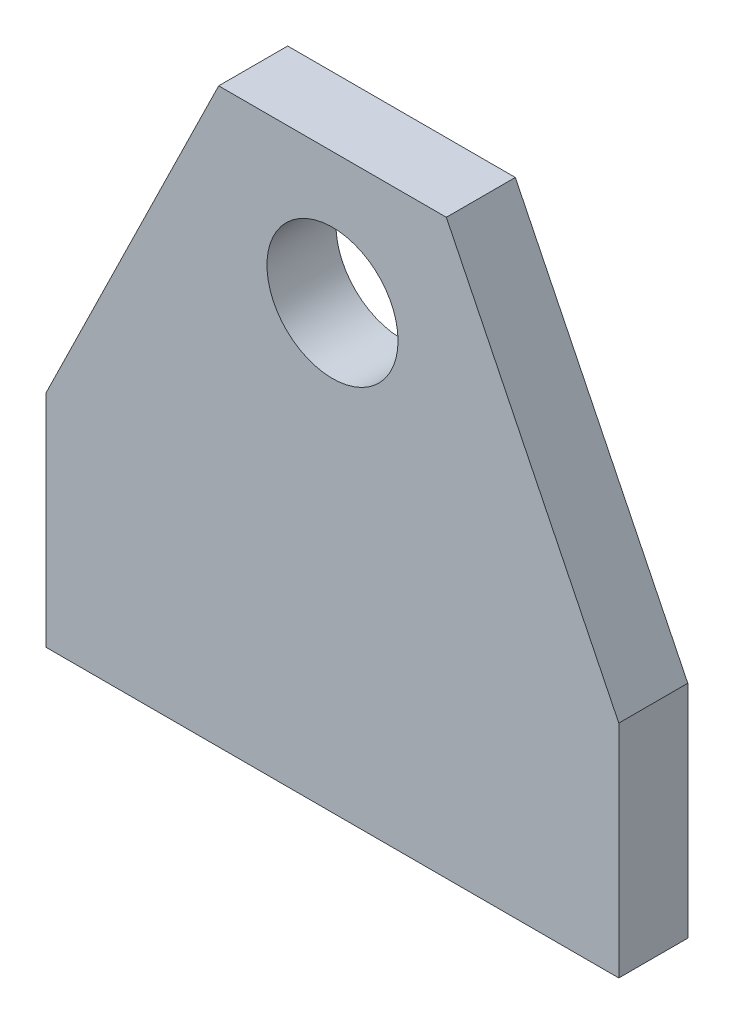
SolidWorks part; units mm, degrees
material "PW20:29:Sc:0:"
ref_plane "Front" through (0, 0, 0) normal (0, 0, 1) x (1, 0, 0)
ref_plane "Top" through (0, 0, 0) normal (0, 1, 0) x (1, 0, 0)
ref_plane "Right" through (0, 0, 0) normal (1, 0, 0) x (0, 0, -1)
sketch "Sketch1" plane through (0, 0, 0) normal (0, 0, 1) x (1, 0, 0)
  line L0 (0, 0) -> (0, 74.0054) construction
  line L1 (-16.5, 83) -> (16.5, 83)
  line L2 (16.5, 83) -> (41.5, 32)
  line L3 (-16.5, 83) -> (-41.5, 32)
  line L4 (41.5, 32) -> (41.5, 0)
  line L5 (-41.5, 32) -> (-41.5, 0)
  line L6 (41.5, 0) -> (-41.5, 0)
  line L7 (0, 0) -> (99.2345, 0) construction
  circle A0 centre (0, 64) radius 9.5
  dimension "D6" = 19
  dimension "D1" = 83
  dimension "D2" = 83
  dimension "D3" = 51
  dimension "D4" = 25
  dimension "D5" = 64
extrude "Base-Extrude" add sketch "Sketch1" along normal blind 10
